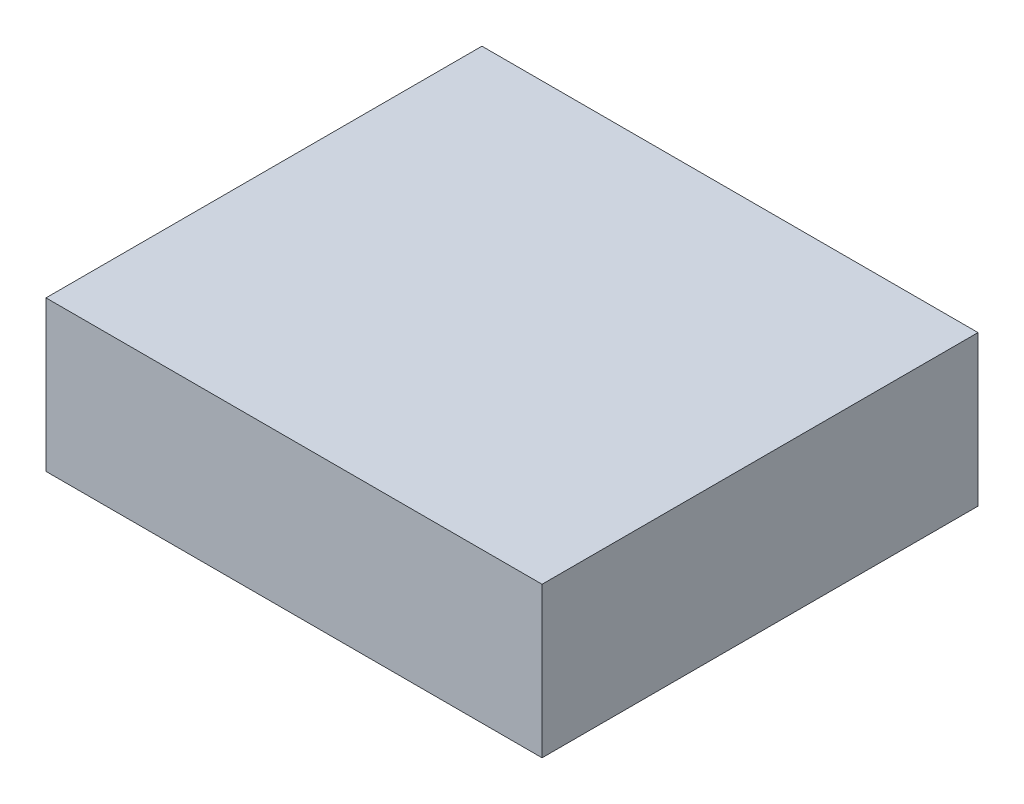
SolidWorks part; units mm, degrees
ref_plane "Спереди" through (0, 0, 0) normal (0, 0, 1) x (1, 0, 0)
ref_plane "Сверху" through (0, 0, 0) normal (0, 1, 0) x (1, 0, 0)
ref_plane "Справа" through (0, 0, 0) normal (1, 0, 0) x (0, 0, -1)
other "Configuration Table"
sketch "Эскиз1" plane through (0, 0, 0) normal (0, 1, 0) x (1, 0, 0)
  line L1 (-16.5, -14.5) -> (16.5, -14.5)
  line L2 (-16.5, -14.5) -> (-16.5, 14.5)
  line L3 (-16.5, 14.5) -> (16.5, 14.5)
  line L4 (16.5, -14.5) -> (16.5, 14.5)
  line L5 (-16.5, -14.5) -> (16.5, 14.5) construction
  line L6 (-16.5, 14.5) -> (16.5, -14.5) construction
  point P0 (0, 0)
  dimension "D1" = 29
  dimension "D2" = 33
extrude "Бобышка-Вытянуть1" add sketch "Эскиз1" along normal blind 10
